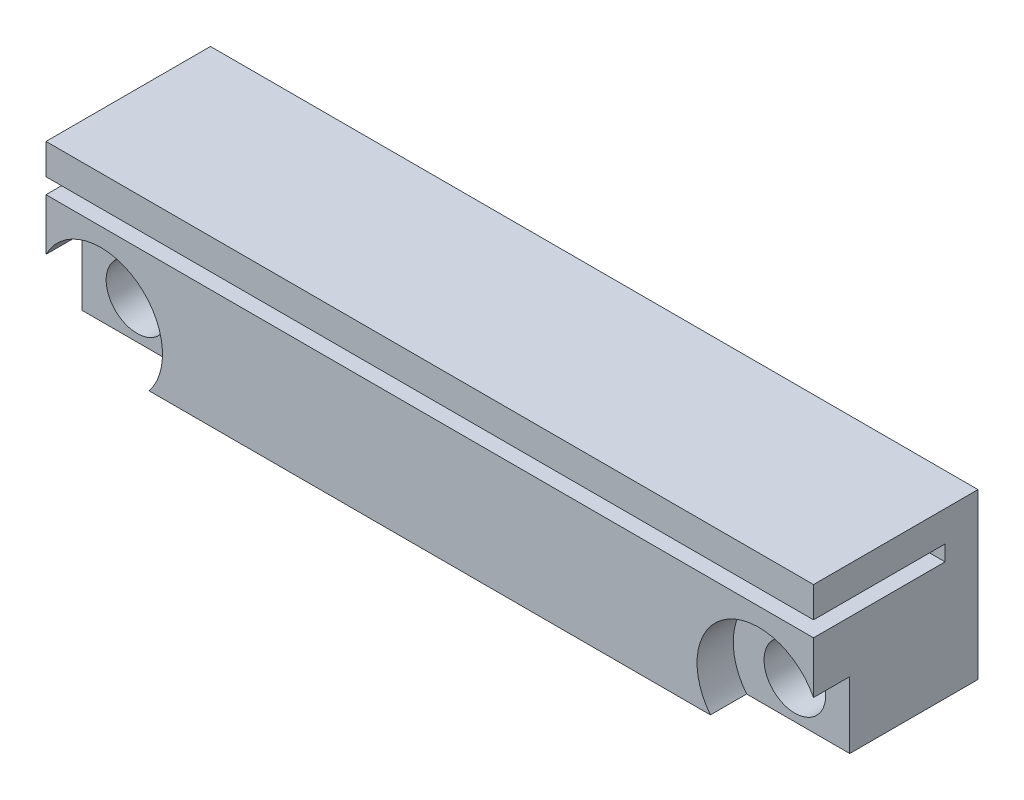
SolidWorks part; units mm, degrees
ref_plane "Front Plane" through (0, 0, 0) normal (0, 0, 1) x (1, 0, 0)
ref_plane "Top Plane" through (0, 0, 0) normal (0, 1, 0) x (1, 0, 0)
ref_plane "Right Plane" through (0, 0, 0) normal (1, 0, 0) x (0, 0, -1)
sketch "Sketch1" plane through (0, 0, 0) normal (0, 0, 1) x (1, 0, 0)
  line L1 (-44.45, 9.525) -> (44.45, 9.525)
  line L2 (-44.45, 9.525) -> (-44.45, -9.525)
  line L3 (-44.45, -9.525) -> (44.45, -9.525)
  line L4 (44.45, 9.525) -> (44.45, -9.525)
  line L5 (-44.45, 9.525) -> (44.45, -9.525) construction
  line L6 (-44.45, -9.525) -> (44.45, 9.525) construction
  point P0 (0, 0)
  dimension "D1" = 88.9
  dimension "D2" = 19.05
extrude "Boss-Extrude1" add sketch "Sketch1" along normal blind 19.05
hole_wizard "CBORE for 1/4 Binding Head Machine Screw1" positions "Sketch2" profile "Sketch4" counterbore size "1/4" standard "ANSI Inch" end condition through all
sketch "Sketch2" plane through (0, 0, 19.05) normal (0, 0, 1) x (1, 0, 0)
  line L0 (-38.1, -5.08) -> (38.1, -5.08) construction
  line L2 (0, 0) -> (0, -5.08) construction
  point P0 (-38.1, -5.08)
  point P2 (38.1, -5.08)
  dimension "D1" = 76.2
  dimension "D2" = 5.08
sketch "Sketch4" plane through (-38.1, -5.08, 19.05) normal (1, 0, 0) x (0, -1, 0)
  line L0 (0, 0) -> (0, 19.05)
  line L1 (0, 19.05) -> (3.5712, 19.05)
  line L3 (3.5712, 19.05) -> (3.5712, 4.191)
  line L4 (3.5712, 4.191) -> (7.1437, 4.191)
  line L5 (7.1437, 4.191) -> (7.1437, 0)
  line L7 (7.1437, 0) -> (0, 0)
  line L11 (0, -6.35) -> (0, 107.95) construction
  dimension "Thru Hole Dia." = 7.1425
  dimension "Thru Hole Depth" = 19.05
  dimension "C'Bore Dia." = 14.2875
  dimension "C'Bore Depth" = 4.191
sketch "Sketch5" plane through (0, 0, 19.05) normal (0, 0, 1) x (1, 0, 0)
  line L1 (-49.1337, 5.98) -> (49.1337, 5.98)
  line L2 (-49.1337, 5.98) -> (-49.1337, 4.18)
  line L3 (-49.1337, 4.18) -> (49.1337, 4.18)
  line L4 (49.1337, 5.98) -> (49.1337, 4.18)
  line L5 (-49.1337, 5.98) -> (49.1337, 4.18) construction
  line L6 (-49.1337, 4.18) -> (49.1337, 5.98) construction
  point P0 (0, 5.08)
  point P5 (0, 5.08)
  point P7 (0, 0)
  dimension "D1" = 1.8
  dimension "D2" = 5.08
extrude "Cut-Extrude1" cut sketch "Sketch5" against normal blind 15.24
sketch "Sketch6" plane through (0, 0, 14.859) normal (0, 0, 1) x (1, 0, 0)
  circle A0 centre (-47.1546, -9.2072) radius 6.1697
  circle A1 centre (49.65, -12.8212) radius 8.7626
extrude "Cut-Extrude2" cut sketch "Sketch6" along normal blind 15.24
